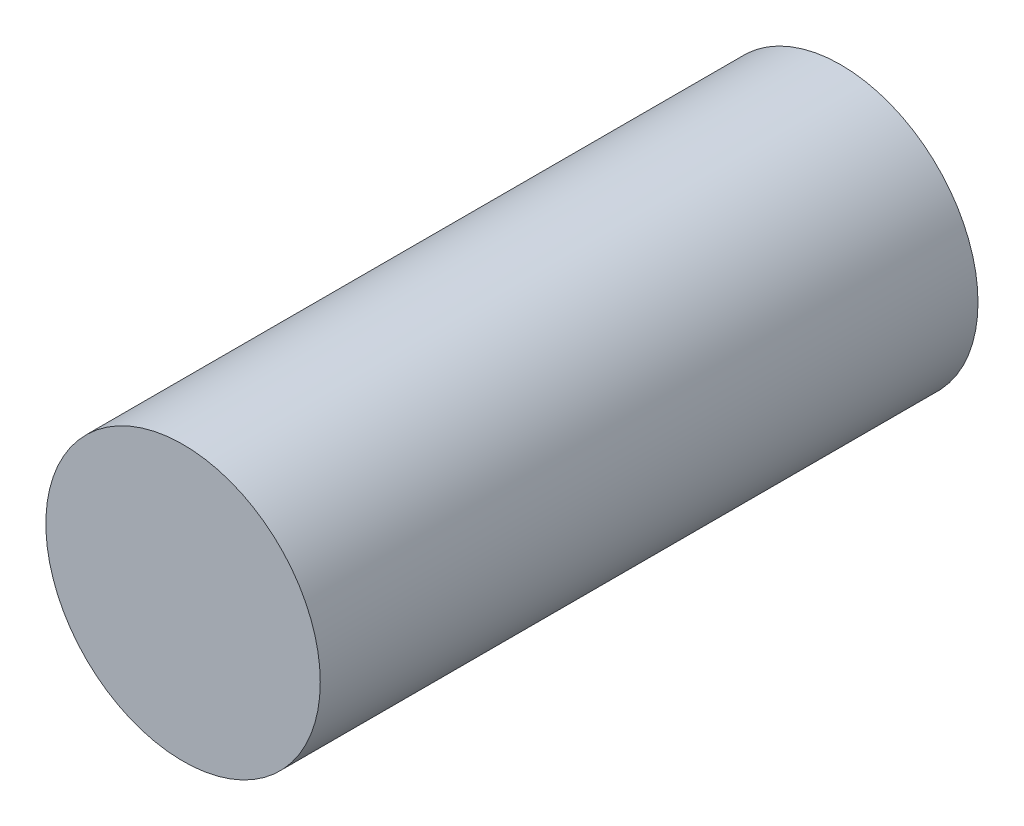
SolidWorks part; units mm, degrees
ref_plane "前视基准面" through (0, 0, 0) normal (0, 0, 1) x (1, 0, 0)
ref_plane "上视基准面" through (0, 0, 0) normal (0, 1, 0) x (1, 0, 0)
ref_plane "右视基准面" through (0, 0, 0) normal (1, 0, 0) x (0, 0, -1)
sketch "草图1" plane through (0, 0, 0) normal (0, 0, 1) x (1, 0, 0)
  circle A0 centre (57.0736, 292.8572) radius 4
extrude "凸台-拉伸1" add sketch "草图1" against normal up to surface (19.174 mm away)
